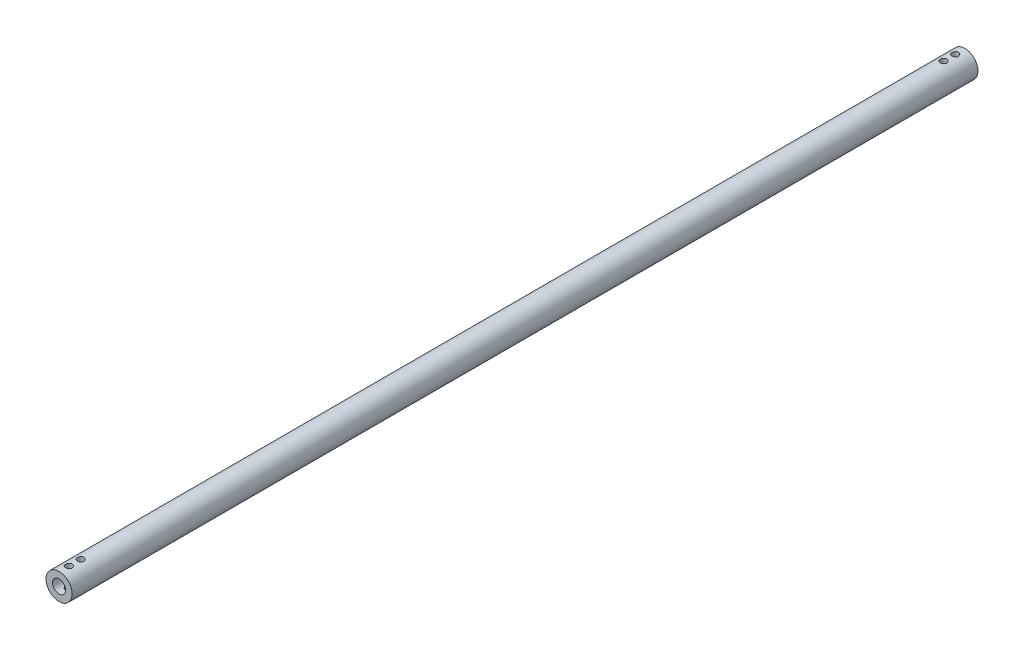
SolidWorks part; units mm, degrees
ref_plane "前视基准面" through (0, 0, 0) normal (0, 0, 1) x (1, 0, 0)
ref_plane "上视基准面" through (0, 0, 0) normal (0, 1, 0) x (1, 0, 0)
ref_plane "右视基准面" through (0, 0, 0) normal (1, 0, 0) x (0, 0, -1)
sketch "草图1" plane through (0, 0, 0) normal (0, 0, 1) x (1, 0, 0)
  circle A0 centre (0, 0) radius 10
  circle A1 centre (0, 0) radius 5
  dimension "D1" = 20
  dimension "D2" = 10
extrude "凸台-拉伸1" add sketch "草图1" along normal blind 694
sketch "草图2" plane through (0, 0, 0) normal (0, 1, 0) x (1, 0, 0)
  line L0 (10, 0) -> (-10, 0) construction
  circle A0 centre (0, -7.5) radius 2.5
  circle A1 centre (0, -16.5) radius 2.5
  circle A2 centre (0, -677.6) radius 2.5
  circle A3 centre (0, -686.5) radius 2.5
  dimension "D1" = 5
  dimension "D2" = 5
  dimension "D3" = 5
  dimension "D4" = 5
  dimension "D5" = 7.5
  dimension "D6" = 16.5
  dimension "D7" = 677.6
  dimension "D8" = 686.5
extrude "切除-拉伸1" cut sketch "草图2" against normal through all both and the other way through all
